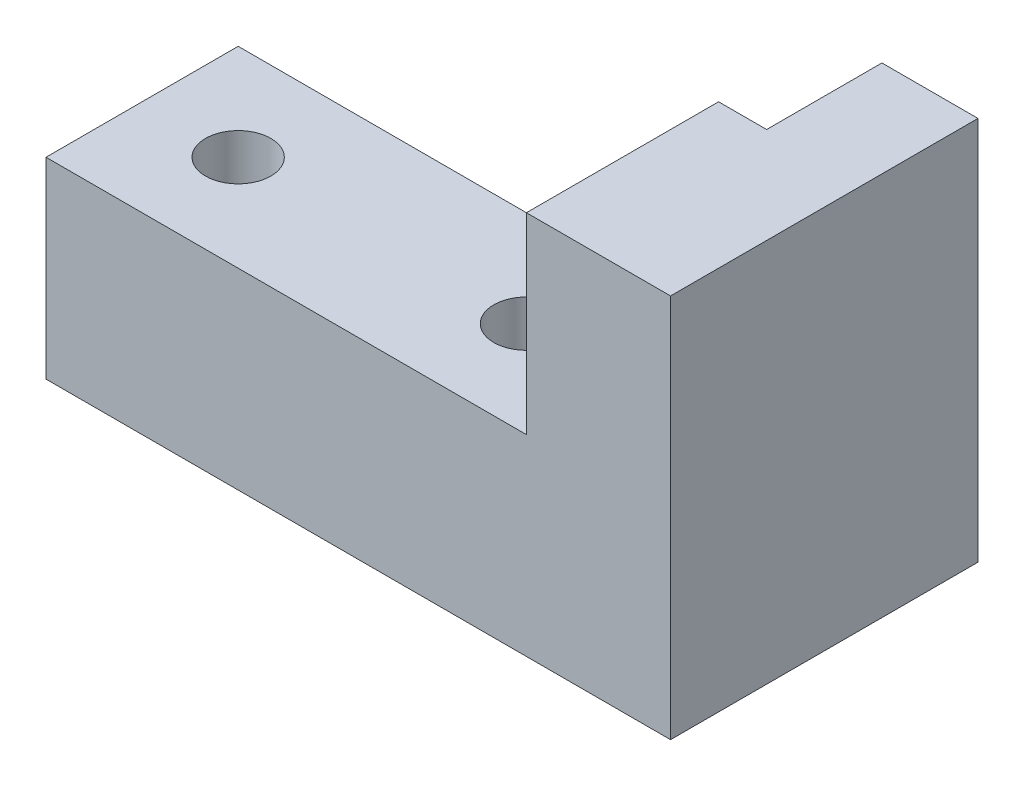
SolidWorks part; units mm, degrees
material "PETG"
ref_plane "Front Plane" through (0, 0, 0) normal (0, 0, 1) x (1, 0, 0)
ref_plane "Top Plane" through (0, 0, 0) normal (0, 1, 0) x (1, 0, 0)
ref_plane "Right Plane" through (0, 0, 0) normal (1, 0, 0) x (0, 0, -1)
sketch "Sketch1" plane through (0, 0, 0) normal (0, 1, 0) x (1, 0, 0)
  line L0 (-7.5, 0) -> (-12.5, 0) construction
  line L1 (-12.5, 5) -> (12.5, 5)
  line L2 (-12.5, 5) -> (-12.5, -5)
  line L3 (-12.5, -5) -> (12.5, -5)
  line L4 (12.5, 5) -> (12.5, -5)
  line L5 (-12.5, 5) -> (12.5, -5) construction
  line L6 (-12.5, -5) -> (12.5, 5) construction
  line L7 (7.5, 0) -> (12.5, 0) construction
  circle A0 centre (-7.5, 0) radius 1.7
  circle A1 centre (7.5, 0) radius 1.7
  point P4 (0, 0)
  dimension "D1" = 3.4
  dimension "D2" = 25
  dimension "D3" = 10
  dimension "D4" = 15
extrude "Boss-Extrude1" add sketch "Sketch1" along normal blind 10
sketch "Sketch2" plane through (0, 0, 0) normal (0, 1, 0) x (1, 0, 0)
  line L0 (12.5, 5) -> (-12.5, 5) construction
  line L6 (12.5, -5) -> (20, -5)
  line L7 (12.5, -5) -> (12.5, 5)
  line L8 (12.5, 5) -> (15, 5)
  line L13 (20, -5) -> (20, 11)
  line L14 (20, 11) -> (15, 11)
  line L15 (15, 5) -> (15, 11)
  dimension "D1" = 15
  dimension "D2" = 5
  dimension "D3" = 6
extrude "Boss-Extrude2" add sketch "Sketch2" along normal blind 20
move or copy body "Body-Move/Copy1" [suppressed] bodies to move or copy 102
